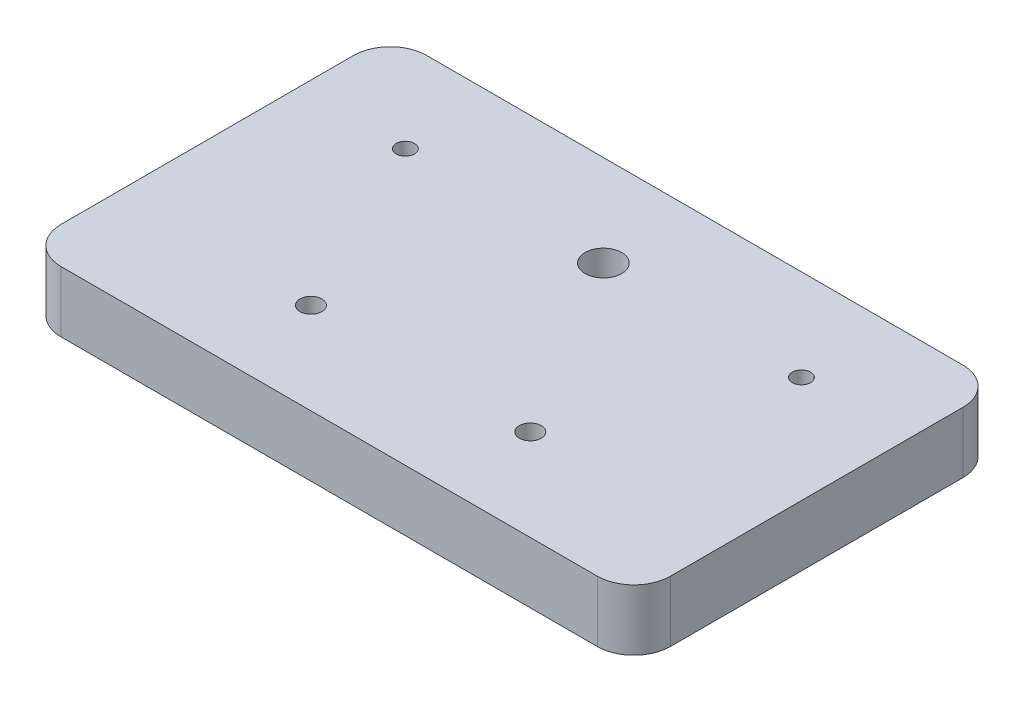
SolidWorks part; units mm, degrees
ref_plane "Front Plane" through (0, 0, 0) normal (0, 0, 1) x (1, 0, 0)
ref_plane "Top Plane" through (0, 0, 0) normal (0, 1, 0) x (1, 0, 0)
ref_plane "Right Plane" through (0, 0, 0) normal (1, 0, 0) x (0, 0, -1)
sketch "Sketch1" plane through (0, 0, 0) normal (0, 1, 0) x (1, 0, 0)
  line L1 (-50, -30) -> (50, -30)
  line L2 (-50, -30) -> (-50, 30)
  line L3 (-50, 30) -> (50, 30)
  line L4 (50, -30) -> (50, 30)
  line L5 (-50, -30) -> (50, 30) construction
  line L6 (-50, 30) -> (50, -30) construction
  point P0 (0, 0)
  dimension "D1" = 60
  dimension "D2" = 100
extrude "Boss-Extrude1" add sketch "Sketch1" along normal blind 10
hole_wizard "CBORE for M3 SHCS1" positions "Sketch3" profile "Sketch4" counterbore size "M3" standard "ANSI Metric" end condition through all
sketch "Sketch3" plane through (0, 0, 0) normal (0, -1, 0) x (-1, 0, 0)
  line L0 (50, -30) -> (-50, -30) construction
  point P0 (-18, -15)
  point P2 (18, -15)
  dimension "D1" = 18
  dimension "D2" = 18
  dimension "D3" = 15
sketch "Sketch4" plane through (18, 0, 15) normal (1, 0, 0) x (0, 0, -1)
  line L0 (0, 0) -> (0, 10)
  line L1 (0, 10) -> (1.8, 10)
  line L3 (1.8, 10) -> (1.8, 3)
  line L4 (1.8, 3) -> (3.25, 3)
  line L5 (3.25, 3) -> (3.25, 0)
  line L7 (3.25, 0) -> (0, 0)
  line L11 (0, -6.35) -> (0, 107.95) construction
  dimension "Thru Hole Dia." = 3.6
  dimension "Thru Hole Depth" = 10
  dimension "C'Bore Dia." = 6.5
  dimension "C'Bore Depth" = 3
sketch "Sketch5" plane through (0, 0, 0) normal (0, -1, 0) x (-1, 0, 0)
  line L0 (-50, 30) -> (50, 30) construction
  circle A0 centre (0, 15) radius 3
  circle A1 centre (32.5, 15) radius 1.5
  circle A2 centre (-32.5, 15) radius 1.5
  dimension "D1" = 6
  dimension "D3" = 3
  dimension "D2" = 15
  dimension "D4" = 32.5
  dimension "D5" = 32.5
extrude "Cut-Extrude1" cut sketch "Sketch5" against normal up to next
fillet "Fillet1" radius 6 4 edges at (-50, 5, 30) (50, 5, 30) (50, 5, -30) (-50, 5, -30)
